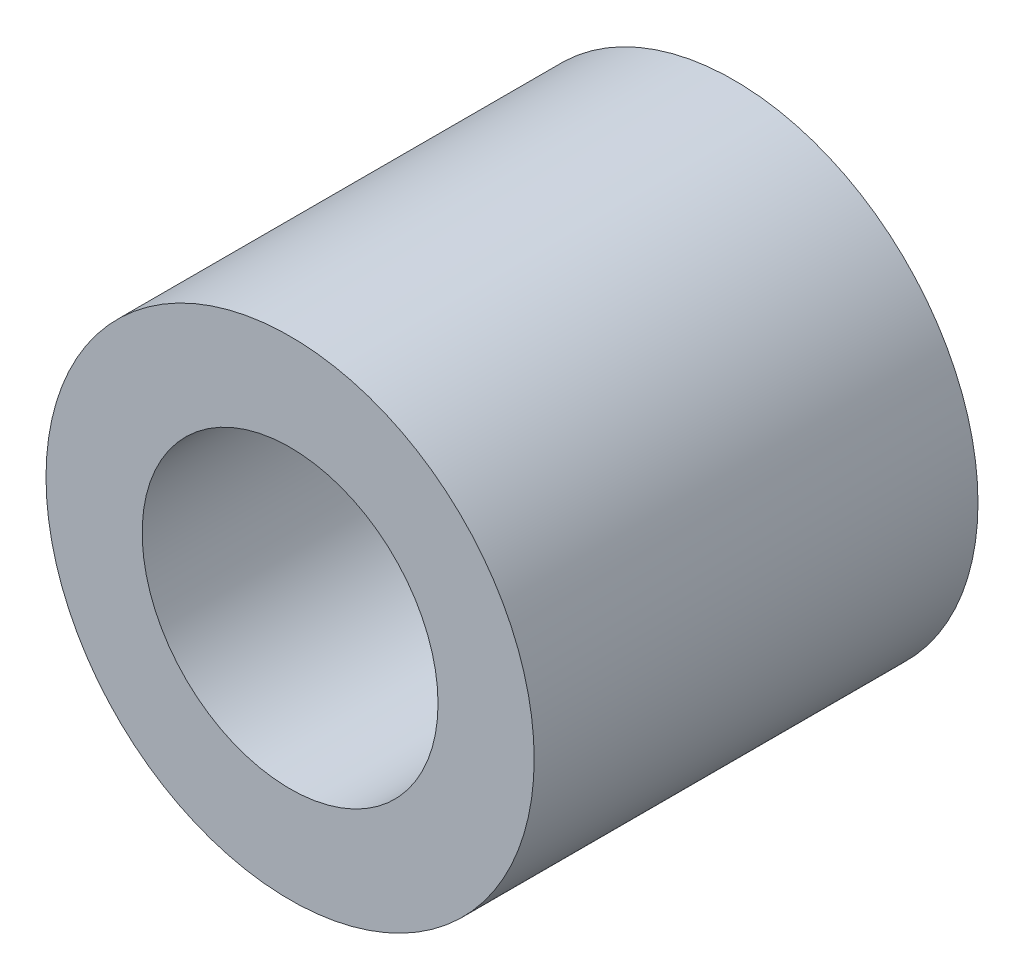
SolidWorks part; units mm, degrees
ref_plane "Plan de face" through (0, 0, 0) normal (0, 0, 1) x (1, 0, 0)
ref_plane "Plan de dessus" through (0, 0, 0) normal (0, 1, 0) x (1, 0, 0)
ref_plane "Plan de droite" through (0, 0, 0) normal (1, 0, 0) x (0, 0, -1)
sketch "Esquisse1" plane through (0, 0, 0) normal (0, 0, 1) x (1, 0, 0)
  circle A0 centre (0, 0) radius 8.25
  circle A1 centre (0, 0) radius 5
  dimension "D1" = 10
  dimension "D2" = 16.5
extrude "Boss.-Extru.1" add sketch "Esquisse1" along normal blind 15
